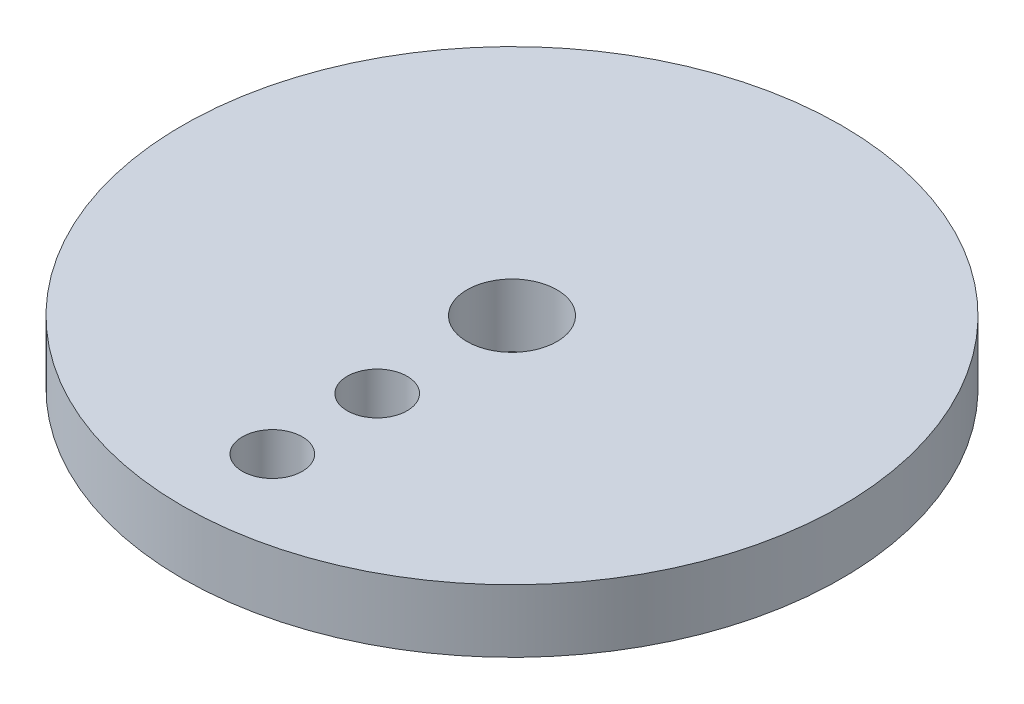
SolidWorks part; units mm, degrees
ref_plane "Front Plane" through (0, 0, 0) normal (0, 0, 1) x (1, 0, 0)
ref_plane "Top Plane" through (0, 0, 0) normal (0, 1, 0) x (1, 0, 0)
ref_plane "Right Plane" through (0, 0, 0) normal (1, 0, 0) x (0, 0, -1)
sketch "Sketch2" plane through (0, 0, 0) normal (0, 1, 0) x (1, 0, 0)
  line L0 (0, -22.5) -> (0, 22.5) construction
  line L1 (0, 22.5) -> (0, 0.5)
  circle A0 centre (0, 11.5) radius 1.5
  circle A1 centre (0, 11.5) radius 11
  circle A2 centre (0, 3.5) radius 1
  circle A4 centre (0, 7) radius 1
  point P8 (0, 0)
  dimension "D1" = 0.5
  dimension "D2" = 22
  dimension "D3" = 3
  dimension "D4" = 3
  dimension "D7" = 3.5
  dimension "D5" = 2
extrude "Boss-Extrude1" add sketch "Sketch2" along normal blind 2.1 contours L1 A1 | L1 A1
